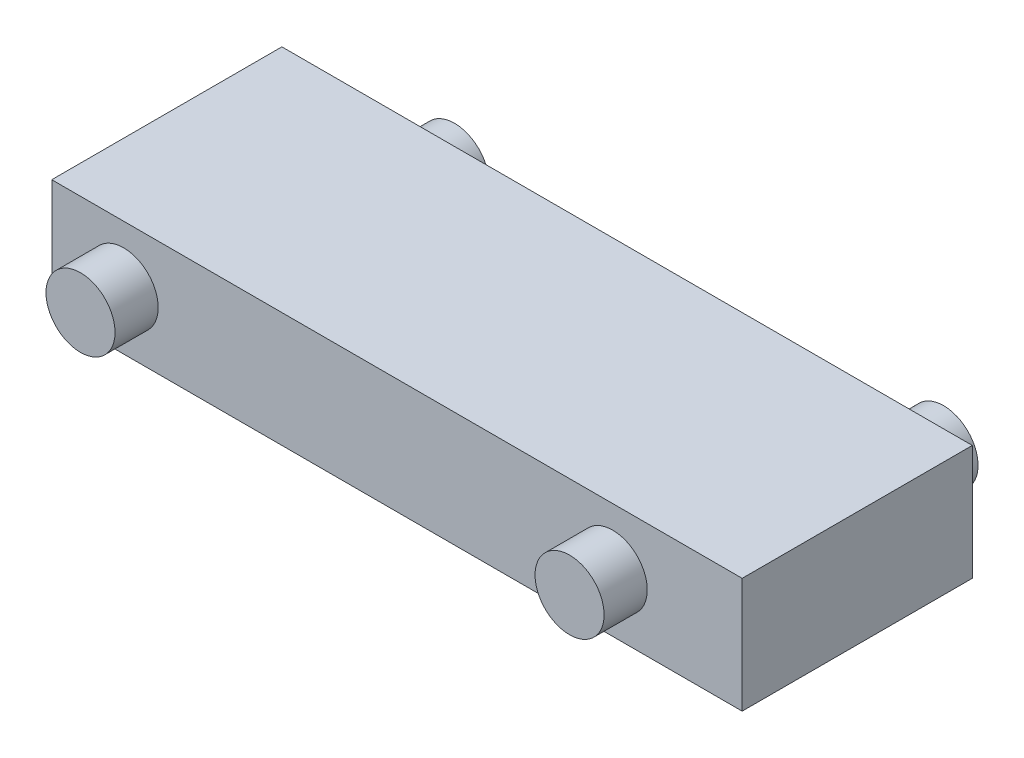
SolidWorks part; units mm, degrees
ref_plane "前视基准面" through (0, 0, 0) normal (0, 0, 1) x (1, 0, 0)
ref_plane "上视基准面" through (0, 0, 0) normal (0, 1, 0) x (1, 0, 0)
ref_plane "右视基准面" through (0, 0, 0) normal (1, 0, 0) x (0, 0, -1)
sketch "草图1" plane through (0, 0, 0) normal (0, 0, 1) x (1, 0, 0)
  line L1 (0, 0) -> (240, 0)
  line L2 (0, 0) -> (0, 40)
  line L3 (0, 40) -> (240, 40)
  line L4 (240, 0) -> (240, 40)
  point P5 (0, 0)
extrude "凸台-拉伸1" add sketch "草图1" along normal blind 80
sketch "草图2" plane through (0, 0, 0) normal (0, 0, -1) x (-1, 0, 0)
  circle A0 centre (-215, 20) radius 12
  circle A1 centre (-45, 20) radius 12
extrude "凸台-拉伸2" add sketch "草图2" along normal blind 15
sketch "草图3" plane through (0, 0, 80) normal (0, 0, 1) x (1, 0, 0)
  circle A0 centre (25, 20) radius 12
  circle A1 centre (195, 20) radius 12
extrude "凸台-拉伸3" add sketch "草图3" along normal blind 15
